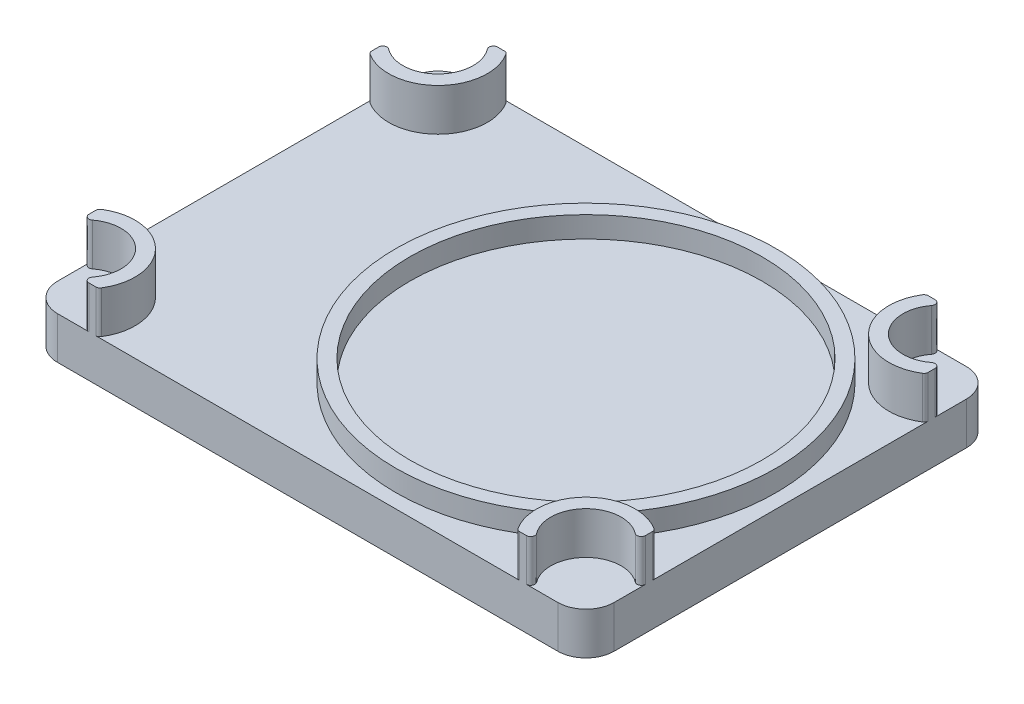
SolidWorks part; units mm, degrees
ref_plane "Front Plane" through (0, 0, 0) normal (0, 0, 1) x (1, 0, 0)
ref_plane "Top Plane" through (0, 0, 0) normal (0, 1, 0) x (1, 0, 0)
ref_plane "Right Plane" through (0, 0, 0) normal (1, 0, 0) x (0, 0, -1)
sketch "Sketch1" plane through (0, 0, 0) normal (0, 1, 0) x (1, 0, 0)
  line L1 (-129.7071, -25.6587) -> (-90.2071, -25.6587)
  line L2 (-129.7071, -25.6587) -> (-129.7071, -54.6587)
  line L3 (-129.7071, -54.6587) -> (-90.2071, -54.6587)
  line L4 (-90.2071, -25.6587) -> (-90.2071, -54.6587)
extrude "Boss-Extrude1" add sketch "Sketch1" along normal blind 3
sketch "Sketch2" plane through (0, 3, 0) normal (0, 1, 0) x (1, 0, 0)
  line L0 (-90.2071, -40.1587) -> (-104.7071, -40.1587)
  line L1 (-90.2071, -54.6587) -> (-90.2071, -25.6587) construction
  circle A0 centre (-104.7071, -40.1587) radius 13.5
  circle A1 centre (-104.7071, -40.1587) radius 12.5
extrude "Boss-Extrude3" add sketch "Sketch2" along normal blind 1.5
sketch "Sketch3" plane through (0, 3, 0) normal (0, 1, 0) x (1, 0, 0)
  line L1 (-129.7071, -25.6587) -> (-127.7071, -25.6587)
  line L2 (-129.7071, -25.6587) -> (-129.7071, -27.6587)
  line L3 (-129.7071, -27.6587) -> (-127.7071, -27.6587)
  line L4 (-127.7071, -25.6587) -> (-127.7071, -27.6587)
  line L5 (-129.7071, -54.6587) -> (-127.7071, -54.6587)
  line L6 (-129.7071, -54.6587) -> (-129.7071, -52.6587)
  line L7 (-129.7071, -52.6587) -> (-127.7071, -52.6587)
  line L8 (-127.7071, -54.6587) -> (-127.7071, -52.6587)
  line L9 (-90.2071, -25.6587) -> (-92.2071, -25.6587)
  line L10 (-90.2071, -25.6587) -> (-90.2071, -27.6587)
  line L11 (-90.2071, -27.6587) -> (-92.2071, -27.6587)
  line L12 (-92.2071, -25.6587) -> (-92.2071, -27.6587)
  line L13 (-90.2071, -54.6587) -> (-92.2071, -54.6587)
  line L14 (-90.2071, -54.6587) -> (-90.2071, -52.6587)
  line L15 (-90.2071, -52.6587) -> (-92.2071, -52.6587)
  line L16 (-92.2071, -54.6587) -> (-92.2071, -52.6587)
  line L18 (-90.2071, -54.6587) -> (-129.7071, -54.6587)
  line L20 (-90.2071, -54.6587) -> (-90.2071, -25.6587)
  line L21 (-90.2071, -25.6587) -> (-129.7071, -25.6587)
  line L22 (-129.7071, -54.6587) -> (-129.7071, -25.6587)
  circle A0 centre (-127.7071, -27.6587) radius 2.5
  circle A1 centre (-127.7071, -27.6587) radius 3.5
  circle A2 centre (-127.7071, -52.6587) radius 2.5
  circle A3 centre (-127.7071, -52.6587) radius 3.5
  circle A4 centre (-92.2071, -27.6587) radius 2.5
  circle A5 centre (-92.2071, -27.6587) radius 3.5
  circle A6 centre (-92.2071, -52.6587) radius 3.5
  circle A7 centre (-92.2071, -52.6587) radius 2.5
extrude "Boss-Extrude4" add sketch "Sketch3" along normal blind 3 contours A7 L20 A6 L18 | L18 A3 L22 A2 | L21 A5 L20 A4 | L22 A1 L21 A0
fillet "Fillet1" radius 2 4 edges at (-129.7071, 1.5, 25.6587) (-90.2071, 1.5, 25.6587) (-90.2071, 1.5, 54.6587) (-129.7071, 1.5, 54.6587)
fillet "Fillet2" radius 0.3 16 edges at (-129.7071, 4.5, 30.531) (-129.7071, 4.5, 49.7865) (-129.7071, 4.5, 29.1587) (-126.2071, 4.5, 25.6587) (-124.8348, 4.5, 25.6587) (-95.0793, 4.5, 25.6587) (-93.7071, 4.5, 25.6587) (-90.2071, 4.5, 29.1587) (-90.2071, 4.5, 30.531) (-90.2071, 4.5, 49.7865) (-90.2071, 4.5, 51.1587) (-93.7071, 4.5, 54.6587) (-95.0793, 4.5, 54.6587) (-129.7071, 4.5, 51.1587) (-124.8348, 4.5, 54.6587) (-126.2071, 4.5, 54.6587)
